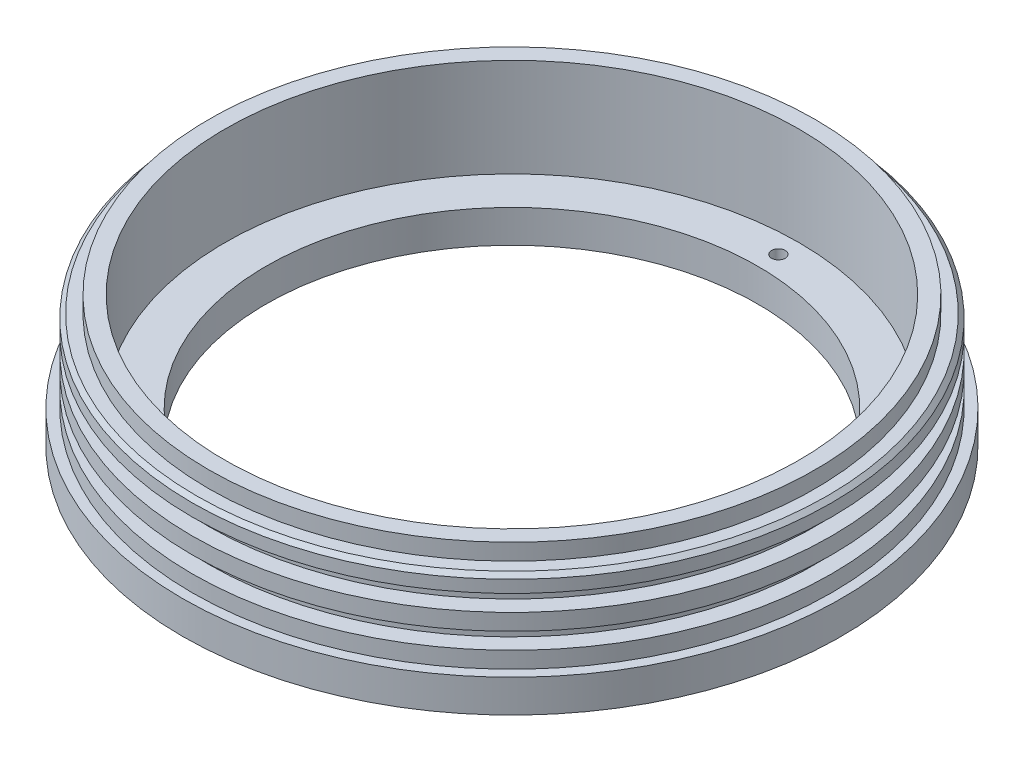
SolidWorks part; units mm, degrees
ref_plane "Front Plane" through (0, 0, 0) normal (0, 0, 1) x (1, 0, 0)
ref_plane "Top Plane" through (0, 0, 0) normal (0, 1, 0) x (1, 0, 0)
ref_plane "Right Plane" through (0, 0, 0) normal (1, 0, 0) x (0, 0, -1)
sketch "Sketch1" plane through (0, 0, 0) normal (0, 1, 0) x (1, 0, 0)
  circle A1 centre (0, 0) radius 51.054
  circle A2 centre (0, 0) radius 38.1
  dimension "D1" = 102.108
  dimension "D2" = 76.2
extrude "Boss-Extrude1" add sketch "Sketch1" along normal blind 5.08
sketch "Sketch2" plane through (0, 5.08, 0) normal (0, 1, 0) x (1, 0, 0)
  circle A0 centre (0, 0) radius 49.53
  circle A1 centre (0, 0) radius 44.45
  dimension "D1" = 88.9
  dimension "D2" = 99.06
extrude "Boss-Extrude2" add sketch "Sketch2" along normal blind 15.24
sketch "Sketch4" plane through (0, 0, 0) normal (0, 0, 1) x (1, 0, 0)
  line L0 (-49.53, 5.08) -> (-49.53, 7.62)
  line L1 (-49.53, 7.62) -> (-46.99, 7.62)
  line L2 (-46.99, 7.62) -> (-46.99, 10.16)
  line L3 (-46.99, 10.16) -> (-49.53, 10.16)
  line L4 (-49.53, 20.32) -> (-49.53, 5.08) construction
  line L5 (-49.53, 10.16) -> (-49.53, 12.7)
  line L6 (-49.53, 12.7) -> (-46.99, 12.7)
  line L7 (-46.99, 12.7) -> (-46.99, 15.24)
  line L8 (-46.99, 15.24) -> (-49.53, 15.24)
  line L9 (-49.53, 15.24) -> (-49.53, 17.78)
  line L10 (-49.53, 17.78) -> (-46.99, 17.78)
  line L11 (-46.99, 17.78) -> (-46.99, 20.32)
  line L12 (49.53, 20.32) -> (-49.53, 20.32) construction
  line L13 (-46.99, 20.32) -> (-49.53, 20.32)
  line L14 (-49.53, 20.32) -> (-49.53, 5.08)
  line L15 (0, 0) -> (0, 62.2914) construction
  line L16 (-51.054, 0) -> (51.054, 0) construction
  dimension "D1" = 2.54
  dimension "D2" = 2.54
revolve "Cut-Revolve1" cut sketch "Sketch4" angle 360 about L15
chamfer "Chamfer1" distance 0.635 angle 45 1 edges at (0, 17.78, -49.53)
sketch "Sketch5" plane through (0, 5.08, 0) normal (0, 1, 0) x (1, 0, 0)
  line L0 (0, 38.1) -> (0, 44.45)
  circle A0 centre (0, 0) radius 38.1 construction
  circle A1 centre (0, 0) radius 44.45 construction
  circle A2 centre (0, 41.275) radius 1.0583
  dimension "D1" = 2.1167
extrude "Cut-Extrude1" cut sketch "Sketch5" against normal blind 26.67 contours L0 A2 | L0 A2
